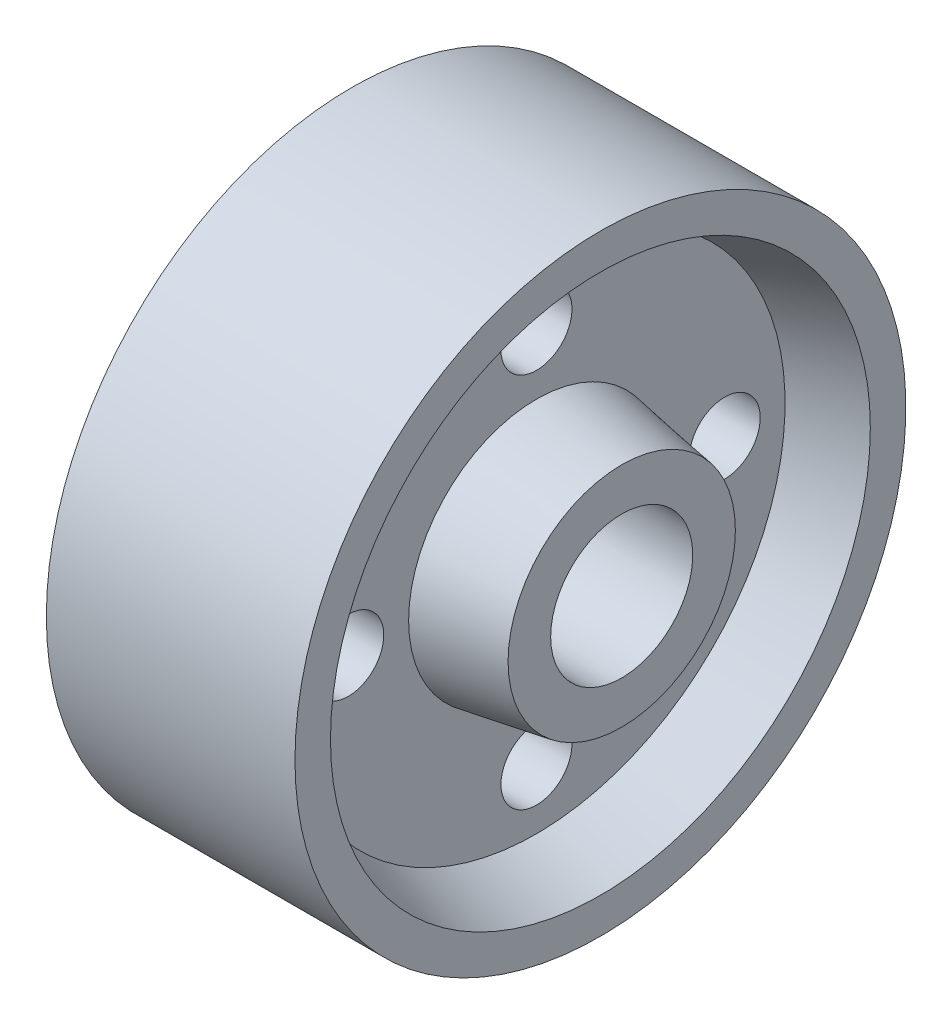
SolidWorks part; units mm, degrees
ref_plane "Front Plane" through (0, 0, 0) normal (0, 0, 1) x (1, 0, 0)
ref_plane "Top Plane" through (0, 0, 0) normal (0, 1, 0) x (1, 0, 0)
ref_plane "Right Plane" through (0, 0, 0) normal (1, 0, 0) x (0, 0, -1)
sketch "Sketch2" plane through (0, 0, 0) normal (0, 1, 0) x (1, 0, 0)
  line L0 (0, 0) -> (3151.0124, 0) construction
  line L1 (0, 0) -> (0, 406.4)
  line L2 (0, 406.4) -> (304.8, 457.2)
  line L3 (304.8, 457.2) -> (304.8, 889)
  line L4 (304.8, 889) -> (76.2, 965.2)
  line L5 (76.2, 965.2) -> (76.2, 1092.2)
  line L6 (76.2, 1092.2) -> (965.2, 1092.2)
  line L7 (520.7, 1092.2) -> (520.7, 0) construction
  line L8 (1041.4, 0) -> (1041.4, 406.4)
  line L9 (1041.4, 406.4) -> (736.6, 457.2)
  line L10 (736.6, 457.2) -> (736.6, 889)
  line L11 (736.6, 889) -> (965.2, 965.2)
  line L12 (965.2, 965.2) -> (965.2, 1092.2)
  line L13 (0, 0) -> (1041.4, 0)
  dimension "D1" = 812.8
  dimension "D2" = 914.4
  dimension "D3" = 1778
  dimension "D4" = 1930.4
  dimension "D5" = 2184.4
  dimension "D6" = 304.8
  dimension "D7" = 444.5
  dimension "D8" = 520.7
revolve "Revolve2" add sketch "Sketch2" angle 360 about L0
sketch "Sketch5" plane through (0, 0, 0) normal (-1, 0, 0) x (0, 0, 1)
  circle A0 centre (0, 0) radius 673.1 construction
  circle A1 centre (0, 673.1) radius 127
  circle A2 centre (673.1, 0) radius 127
  circle A3 centre (0, -673.1) radius 127
  circle A4 centre (-673.1, 0) radius 127
  point P14 (0, 0)
  dimension "D1" = 1346.2
  dimension "D2" = 254
  dimension "D3" = 4
extrude "Cut-Extrude1" cut sketch "Sketch5" against normal through all
sketch "Sketch6" plane through (0, 0, 0) normal (-1, 0, 0) x (0, 0, 1)
  circle A0 centre (0, 0) radius 254
  dimension "D1" = 508
extrude "Cut-Extrude2" cut sketch "Sketch6" against normal through all
